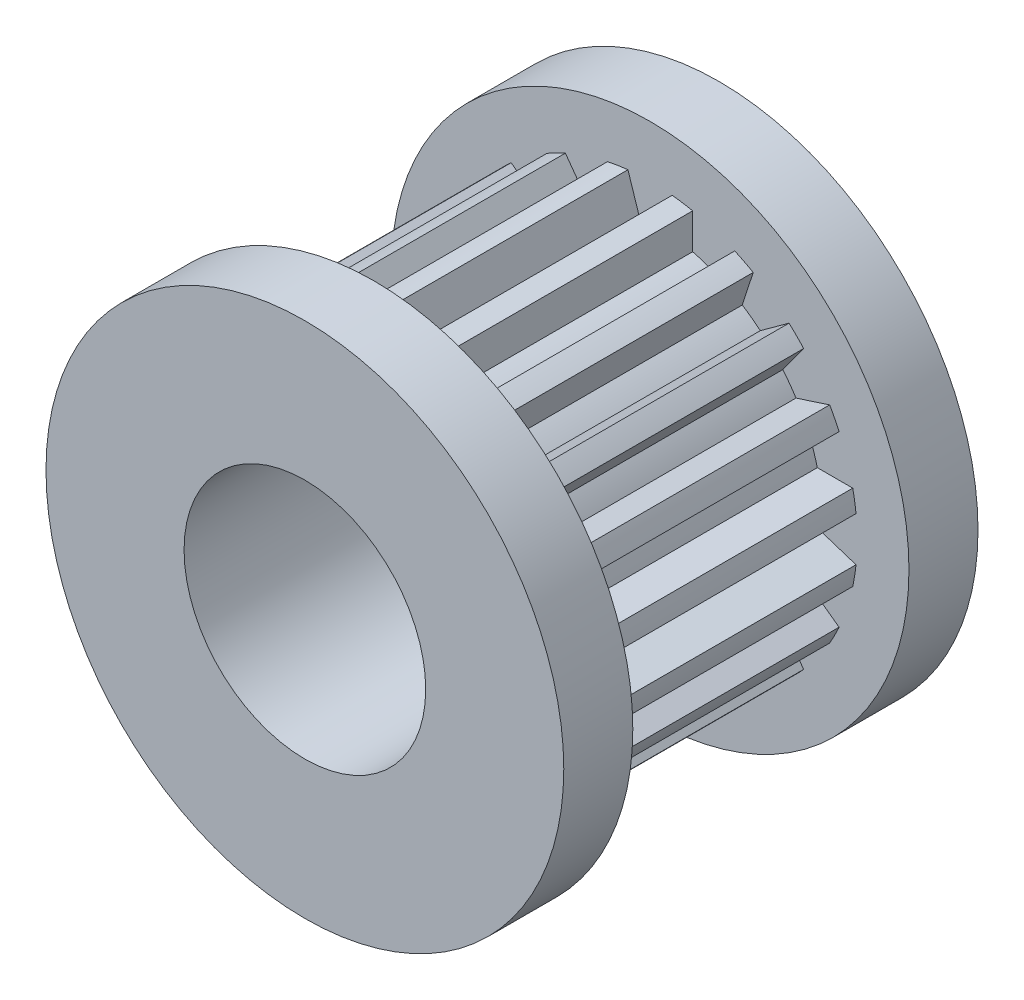
SolidWorks part; units mm, degrees
material "Delrin 2700 NC010, Low Viscosity Acetal Copolymer (SS)"
ref_plane "Front Plane" through (0, 0, 0) normal (0, 0, 1) x (1, 0, 0)
ref_plane "Top Plane" through (0, 0, 0) normal (0, 1, 0) x (1, 0, 0)
ref_plane "Right Plane" through (0, 0, 0) normal (1, 0, 0) x (0, 0, -1)
sketch "Sketch2" plane through (0, 0, 0) normal (0, 0, 1) x (1, 0, 0)
  line L0 (0, 5) -> (0, 6) construction
  line L1 (1.5451, 4.7553) -> (1.8541, 5.7063) construction
  line L2 (0.324, 4.9895) -> (0.6411, 5.9656)
  line L3 (1.2337, 5.8718) -> (1.2337, 4.8454)
  line L4 (0.9386, 5.9261) -> (0.7822, 4.9384) construction
  line L5 (1.8499, 4.6452) -> (2.4532, 5.4755)
  line L6 (2.9878, 5.2032) -> (2.6707, 4.227)
  line L7 (3.1948, 3.8462) -> (4.0252, 4.4495)
  line L8 (4.4495, 4.0252) -> (3.8462, 3.1948)
  line L9 (4.227, 2.6707) -> (5.2032, 2.9878)
  line L10 (5.4755, 2.4532) -> (4.6452, 1.8499)
  line L11 (4.8454, 1.2337) -> (5.8718, 1.2337)
  line L12 (5.9656, 0.6411) -> (4.9895, 0.324)
  line L13 (4.9895, -0.324) -> (5.9656, -0.6411)
  line L14 (5.8718, -1.2337) -> (4.8454, -1.2337)
  line L15 (4.6452, -1.8499) -> (5.4755, -2.4532)
  line L16 (5.2032, -2.9878) -> (4.227, -2.6707)
  line L17 (3.8462, -3.1948) -> (4.4495, -4.0252)
  line L18 (4.0252, -4.4495) -> (3.1948, -3.8462)
  line L19 (2.6707, -4.227) -> (2.9878, -5.2032)
  line L20 (2.4532, -5.4755) -> (1.8499, -4.6452)
  line L21 (1.2337, -4.8454) -> (1.2337, -5.8718)
  line L22 (0.6411, -5.9656) -> (0.324, -4.9895)
  line L23 (-0.324, -4.9895) -> (-0.6411, -5.9656)
  line L24 (-1.2337, -5.8718) -> (-1.2337, -4.8454)
  line L25 (-1.8499, -4.6452) -> (-2.4532, -5.4755)
  line L26 (-2.9878, -5.2032) -> (-2.6707, -4.227)
  line L27 (-3.1948, -3.8462) -> (-4.0252, -4.4495)
  line L28 (-4.4495, -4.0252) -> (-3.8462, -3.1948)
  line L29 (-4.227, -2.6707) -> (-5.2032, -2.9878)
  line L30 (-5.4755, -2.4532) -> (-4.6452, -1.8499)
  line L31 (-4.8454, -1.2337) -> (-5.8718, -1.2337)
  line L32 (-5.9656, -0.6411) -> (-4.9895, -0.324)
  line L33 (-4.9895, 0.324) -> (-5.9656, 0.6411)
  line L34 (-5.8718, 1.2337) -> (-4.8454, 1.2337)
  line L35 (-4.6452, 1.8499) -> (-5.4755, 2.4532)
  line L36 (-5.2032, 2.9878) -> (-4.227, 2.6707)
  line L37 (-3.8462, 3.1948) -> (-4.4495, 4.0252)
  line L38 (-4.0252, 4.4495) -> (-3.1948, 3.8462)
  line L39 (-2.6707, 4.227) -> (-2.9878, 5.2032)
  line L40 (-2.4532, 5.4755) -> (-1.8499, 4.6452)
  line L41 (-1.2337, 4.8454) -> (-1.2337, 5.8718)
  line L42 (-0.6411, 5.9656) -> (-0.324, 4.9895)
  arc A2 (1.2337, 5.8718) -> (0.6411, 5.9656) centre (0, 0) ccw
  arc A3 (1.5451, 4.7553) -> (1.2337, 4.8454) centre (0, 0) ccw
  arc A4 (0.324, 4.9895) -> (0, 5) centre (0, 0) ccw
  arc A5 (1.8499, 4.6452) -> (1.5451, 4.7553) centre (0, 0) ccw
  arc A6 (2.9878, 5.2032) -> (2.4532, 5.4755) centre (0, 0) ccw
  arc A7 (2.9389, 4.0451) -> (2.6707, 4.227) centre (0, 0) ccw
  arc A8 (3.1948, 3.8462) -> (2.9389, 4.0451) centre (0, 0) ccw
  arc A9 (4.4495, 4.0252) -> (4.0252, 4.4495) centre (0, 0) ccw
  arc A10 (4.0451, 2.9389) -> (3.8462, 3.1948) centre (0, 0) ccw
  arc A11 (4.227, 2.6707) -> (4.0451, 2.9389) centre (0, 0) ccw
  arc A12 (5.4755, 2.4532) -> (5.2032, 2.9878) centre (0, 0) ccw
  arc A13 (4.7553, 1.5451) -> (4.6452, 1.8499) centre (0, 0) ccw
  arc A14 (4.8454, 1.2337) -> (4.7553, 1.5451) centre (0, 0) ccw
  arc A15 (5.9656, 0.6411) -> (5.8718, 1.2337) centre (0, 0) ccw
  arc A16 (5, 0) -> (4.9895, 0.324) centre (0, 0) ccw
  arc A17 (4.9895, -0.324) -> (5, 0) centre (0, 0) ccw
  arc A18 (5.8718, -1.2337) -> (5.9656, -0.6411) centre (0, 0) ccw
  arc A19 (4.7553, -1.5451) -> (4.8454, -1.2337) centre (0, 0) ccw
  arc A20 (4.6452, -1.8499) -> (4.7553, -1.5451) centre (0, 0) ccw
  arc A21 (5.2032, -2.9878) -> (5.4755, -2.4532) centre (0, 0) ccw
  arc A22 (4.0451, -2.9389) -> (4.227, -2.6707) centre (0, 0) ccw
  arc A23 (3.8462, -3.1948) -> (4.0451, -2.9389) centre (0, 0) ccw
  arc A24 (4.0252, -4.4495) -> (4.4495, -4.0252) centre (0, 0) ccw
  arc A25 (2.9389, -4.0451) -> (3.1948, -3.8462) centre (0, 0) ccw
  arc A26 (2.6707, -4.227) -> (2.9389, -4.0451) centre (0, 0) ccw
  arc A27 (2.4532, -5.4755) -> (2.9878, -5.2032) centre (0, 0) ccw
  arc A28 (1.5451, -4.7553) -> (1.8499, -4.6452) centre (0, 0) ccw
  arc A29 (1.2337, -4.8454) -> (1.5451, -4.7553) centre (0, 0) ccw
  arc A30 (0.6411, -5.9656) -> (1.2337, -5.8718) centre (0, 0) ccw
  arc A31 (0, -5) -> (0.324, -4.9895) centre (0, 0) ccw
  arc A32 (-0.324, -4.9895) -> (0, -5) centre (0, 0) ccw
  arc A33 (-1.2337, -5.8718) -> (-0.6411, -5.9656) centre (0, 0) ccw
  arc A34 (-1.5451, -4.7553) -> (-1.2337, -4.8454) centre (0, 0) ccw
  arc A35 (-1.8499, -4.6452) -> (-1.5451, -4.7553) centre (0, 0) ccw
  arc A36 (-2.9878, -5.2032) -> (-2.4532, -5.4755) centre (0, 0) ccw
  arc A37 (-2.9389, -4.0451) -> (-2.6707, -4.227) centre (0, 0) ccw
  arc A38 (-3.1948, -3.8462) -> (-2.9389, -4.0451) centre (0, 0) ccw
  arc A39 (-4.4495, -4.0252) -> (-4.0252, -4.4495) centre (0, 0) ccw
  arc A40 (-4.0451, -2.9389) -> (-3.8462, -3.1948) centre (0, 0) ccw
  arc A41 (-4.227, -2.6707) -> (-4.0451, -2.9389) centre (0, 0) ccw
  arc A42 (-5.4755, -2.4532) -> (-5.2032, -2.9878) centre (0, 0) ccw
  arc A43 (-4.7553, -1.5451) -> (-4.6452, -1.8499) centre (0, 0) ccw
  arc A44 (-4.8454, -1.2337) -> (-4.7553, -1.5451) centre (0, 0) ccw
  arc A45 (-5.9656, -0.6411) -> (-5.8718, -1.2337) centre (0, 0) ccw
  arc A46 (-5, 0) -> (-4.9895, -0.324) centre (0, 0) ccw
  arc A47 (-4.9895, 0.324) -> (-5, 0) centre (0, 0) ccw
  arc A48 (-5.8718, 1.2337) -> (-5.9656, 0.6411) centre (0, 0) ccw
  arc A49 (-4.7553, 1.5451) -> (-4.8454, 1.2337) centre (0, 0) ccw
  arc A50 (-4.6452, 1.8499) -> (-4.7553, 1.5451) centre (0, 0) ccw
  arc A51 (-5.2032, 2.9878) -> (-5.4755, 2.4532) centre (0, 0) ccw
  arc A52 (-4.0451, 2.9389) -> (-4.227, 2.6707) centre (0, 0) ccw
  arc A53 (-3.8462, 3.1948) -> (-4.0451, 2.9389) centre (0, 0) ccw
  arc A54 (-4.0252, 4.4495) -> (-4.4495, 4.0252) centre (0, 0) ccw
  arc A55 (-2.9389, 4.0451) -> (-3.1948, 3.8462) centre (0, 0) ccw
  arc A56 (-2.6707, 4.227) -> (-2.9389, 4.0451) centre (0, 0) ccw
  arc A57 (-2.4532, 5.4755) -> (-2.9878, 5.2032) centre (0, 0) ccw
  arc A58 (-1.5451, 4.7553) -> (-1.8499, 4.6452) centre (0, 0) ccw
  arc A59 (-1.2337, 4.8454) -> (-1.5451, 4.7553) centre (0, 0) ccw
  arc A60 (-0.6411, 5.9656) -> (-1.2337, 5.8718) centre (0, 0) ccw
  arc A61 (0, 5) -> (-0.324, 4.9895) centre (0, 0) ccw
  point P3 (0, 0)
  point P129 (0, 0)
  dimension "D1" = 6
  dimension "D2" = 5
  dimension "D5" = 0.6
  dimension "D3" = 18
  dimension "D4" = 9
  dimension "D6" = 20
extrude "Boss-Extrude1" add sketch "Sketch2" along normal blind 8 contours A4 A61 L42 A60 L41 A59 A58 L40 A57 L39 A56 A55 L38 A54 L37 A53 A52 L36 A51 L35 A50 A49 L34 A48 L33 A47 A46 L32 A45 L31 A44 A43 L30 A42 L29 A41 A40 L28 A39 L27 A38 A37 L26 A36 L25 A35 A34 L24 A33 L23 A32
sketch "Sketch3" plane through (0, 0, 8) normal (0, 0, 1) x (1, 0, 0)
  circle A0 centre (0, 0) radius 7.5
  dimension "D1" = 15
extrude "Boss-Extrude2" add sketch "Sketch3" along normal blind 2
sketch "Sketch4" plane through (0, 0, 0) normal (0, 0, -1) x (-1, 0, 0)
  circle A1 centre (0, 0) radius 7.5
  circle A2 centre (0, 0) radius 7.5
  dimension "D1" = 0
extrude "Boss-Extrude3" add sketch "Sketch4" along normal blind 2
sketch "Sketch5" plane through (0, 0, -2) normal (0, 0, -1) x (-1, 0, 0)
  circle A0 centre (0, 0) radius 3.5
  point P3 (0, 0)
  dimension "D1" = 7
extrude "Cut-Extrude1" cut sketch "Sketch5" against normal through all
